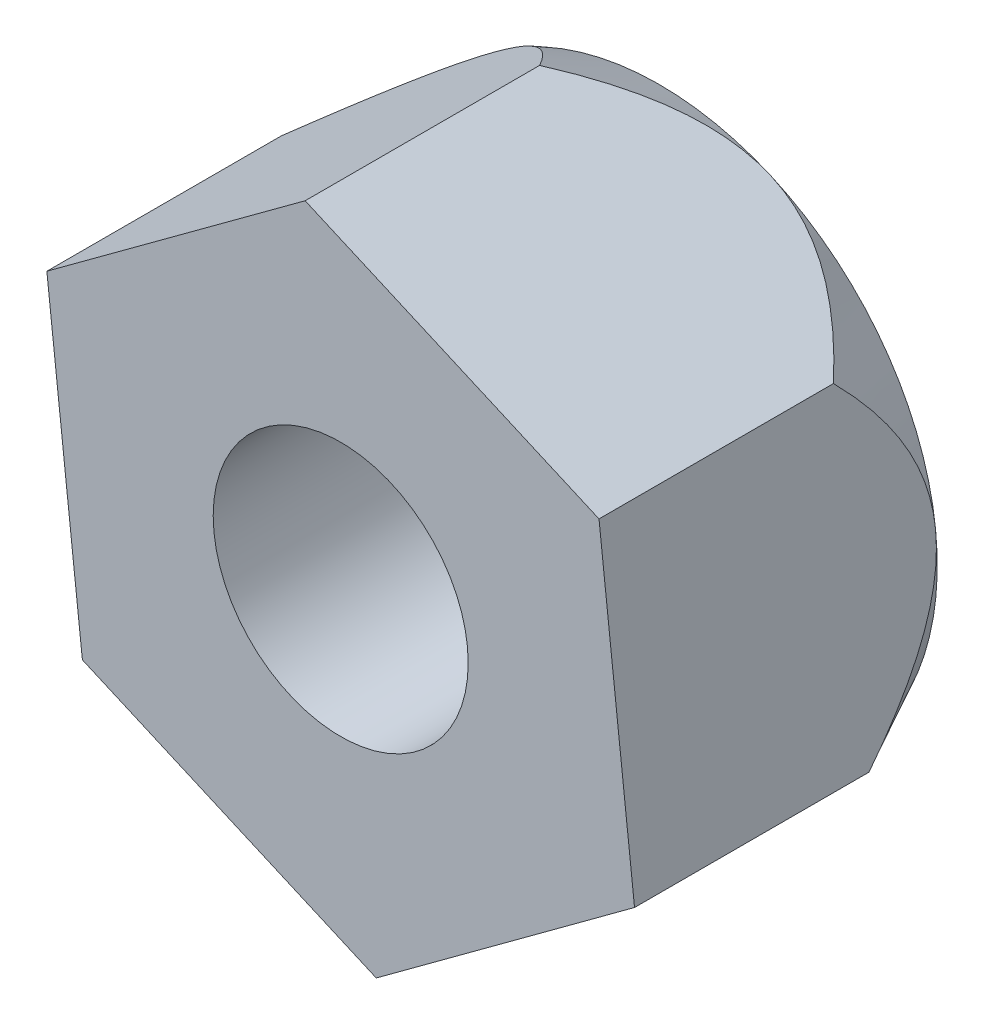
SolidWorks part; units mm, degrees
ref_plane "Front Plane" through (0, 0, 0) normal (0, 0, 1) x (1, 0, 0)
ref_plane "Top Plane" through (0, 0, 0) normal (0, 1, 0) x (1, 0, 0)
ref_plane "Right Plane" through (0, 0, 0) normal (1, 0, 0) x (0, 0, -1)
sketch "Sketch1" plane through (0, 0, 0) normal (0, 0, 1) x (1, 0, 0)
  line L1 (4.6089, -2.0171) -> (4.0513, 2.9829)
  line L2 (4.0513, 2.9829) -> (-0.5576, 5)
  line L3 (-0.5576, 5) -> (-4.6089, 2.0171)
  line L4 (-4.6089, 2.0171) -> (-4.0513, -2.9829)
  line L5 (-4.0513, -2.9829) -> (0.5576, -5)
  line L6 (0.5576, -5) -> (4.6089, -2.0171)
  circle A0 centre (0, 0) radius 2
  circle A1 centre (0, 0) radius 4.357
  dimension "D1" = 4
  dimension "D2" = 5
  dimension "D3" = 4.0513
extrude "Boss-Extrude2" add sketch "Sketch1" along normal blind 5 contours A1 A0 | A1 L6 L1 | A1 L5 L6
sketch "Sketch2" plane through (0, 0, 0) normal (0, 0, -1) x (-1, 0, 0)
  circle A0 centre (0, 0) radius 2
  dimension "D1" = 4
extrude "Cut-Extrude1" cut sketch "Sketch2" against normal through all
sketch "Sketch3" plane through (0, 0, 0) normal (0, 0, -1) x (-1, 0, 0)
  circle A0 centre (0, 0) radius 4.357
extrude "Cut-Extrude2" cut sketch "Sketch3" against normal blind 5 draft 27 flip side to cut
